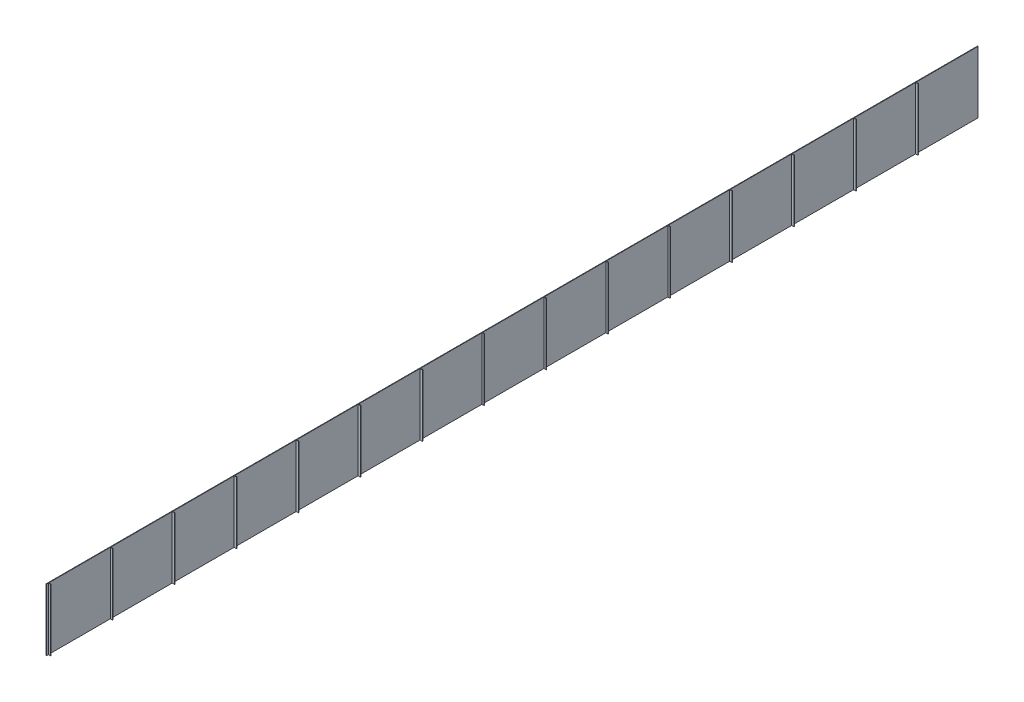
SolidWorks part; units mm, degrees
ref_plane "Front" through (0, 0, 0) normal (0, 0, 1) x (1, 0, 0)
ref_plane "Top" through (0, 0, 0) normal (0, 1, 0) x (1, 0, 0)
ref_plane "Right" through (0, 0, 0) normal (1, 0, 0) x (0, 0, -1)
sketch "草图1" plane through (0, 0, 0) normal (0, 0, 1) x (1, 0, 0)
  line L1 (-1.4, -166.25) -> (1.4, -166.25)
  line L2 (-1.4, -166.25) -> (-1.4, 166.25)
  line L3 (-1.4, 166.25) -> (1.4, 166.25)
  line L4 (1.4, -166.25) -> (1.4, 166.25)
  line L5 (-1.4, -166.25) -> (1.4, 166.25) construction
  line L6 (-1.4, 166.25) -> (1.4, -166.25) construction
  point P0 (0, 0)
extrude "凸台-拉伸1" add sketch "草图1" along normal blind 5000
sketch "草图2" plane through (1.4, 0, 0) normal (1, 0, 0) x (0, 0, -1)
  line L0 (-5000, -166.25) -> (0, -166.25) construction
  line L4 (-332.5, 166.25) -> (-332.5, -166.25)
  line L5 (-332.5, 166.25) -> (-335.3, 166.25)
  line L6 (-5000, 166.25) -> (0, 166.25) construction
  line L7 (-335.3, 166.25) -> (-335.3, -166.25)
  line L8 (-335.3, -166.25) -> (-332.5, -166.25)
extrude "凸台-拉伸2" add sketch "草图2" along normal blind 12.2 separate body
pattern_linear "阵列(线性)1" count 15 spacing 332.5 along (0, 0, 1) of "凸台-拉伸2"
